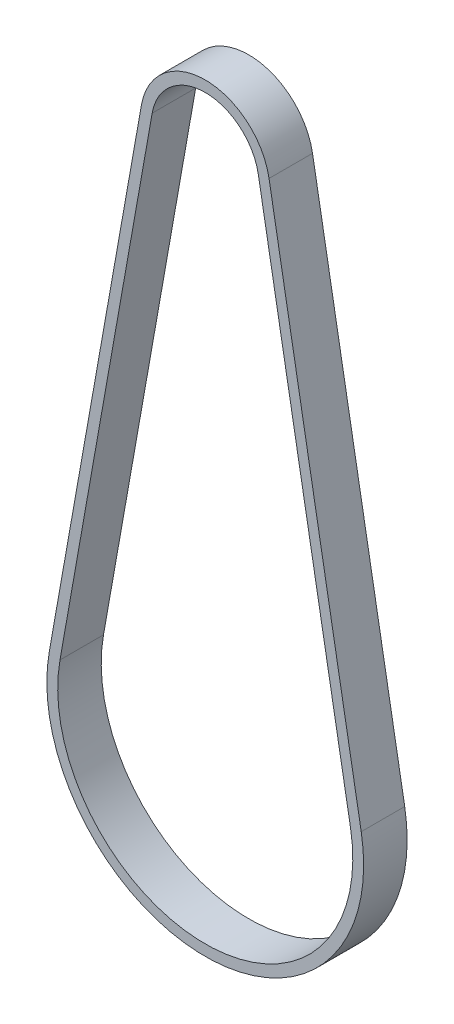
SolidWorks part; units mm, degrees
ref_plane "Front" through (0, 0, 0) normal (0, 0, 1) x (1, 0, 0)
ref_plane "Top" through (0, 0, 0) normal (0, 1, 0) x (1, 0, 0)
ref_plane "Right" through (0, 0, 0) normal (1, 0, 0) x (0, 0, -1)
sketch "Esquisse2" plane through (0, 0, 0) normal (0, 0, 1) x (1, 0, 0)
  line L0 (0, 0) -> (1, 0) construction
  line L1 (0, 0) -> (0, 1) construction
  line L2 (-21.514, -70.1122) -> (-8.7976, 1.5609)
  line L3 (8.7976, 1.5609) -> (21.514, -70.1122)
  arc A0 (21.514, -70.1122) -> (-21.514, -70.1122) centre (0, -73.9292) cw
  arc A1 (-8.7976, 1.5609) -> (8.7976, 1.5609) centre (0, 0) cw
extrude "Extru.-Mince1" add sketch "Esquisse2" along normal blind 6 thin
